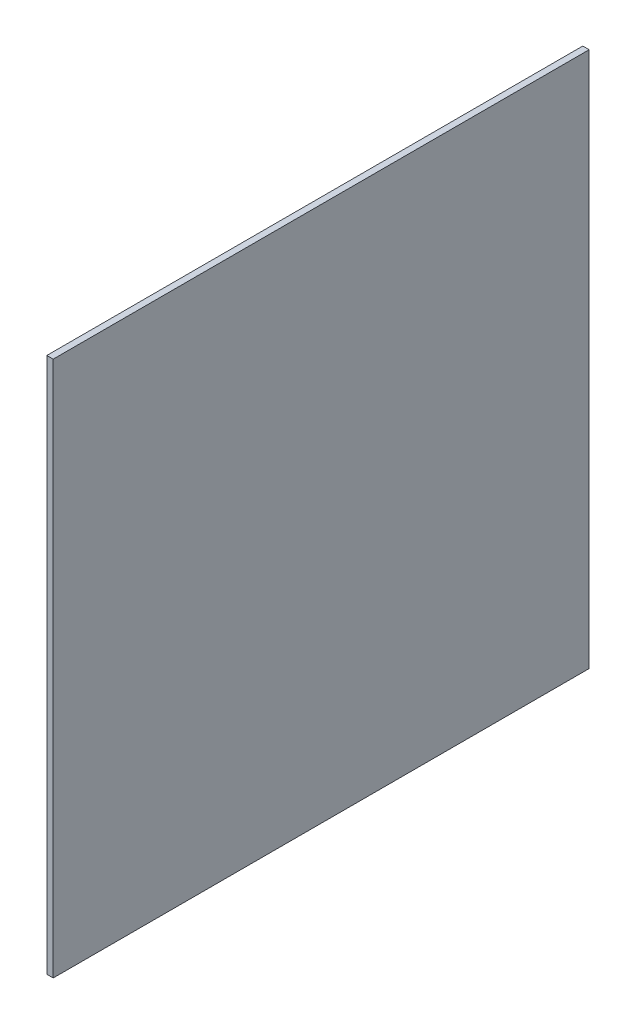
SolidWorks part; units mm, degrees
ref_plane "Front Plane" through (0, 0, 0) normal (0, 0, 1) x (1, 0, 0)
ref_plane "Top Plane" through (0, 0, 0) normal (0, 1, 0) x (1, 0, 0)
ref_plane "Right Plane" through (0, 0, 0) normal (1, 0, 0) x (0, 0, -1)
sketch "Sketch1" plane through (0, 0, 0) normal (1, 0, 0) x (0, 0, -1)
  line L1 (0, 0) -> (133.35, 0)
  line L2 (0, 0) -> (0, 133.35)
  line L3 (0, 133.35) -> (133.35, 133.35)
  line L4 (133.35, 0) -> (133.35, 133.35)
  dimension "D1" = 133.35
  dimension "D2" = 133.35
extrude "Boss-Extrude1" add sketch "Sketch1" along normal blind 1.5875
